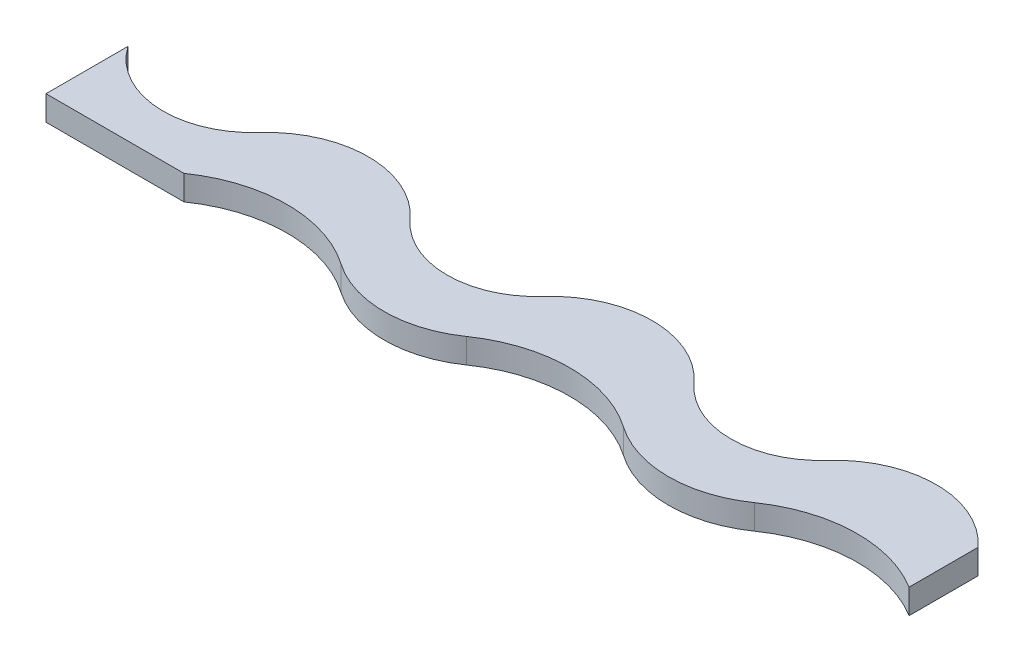
SolidWorks part; units mm, degrees
ref_plane "Front Plane" through (0, 0, 0) normal (0, 0, 1) x (1, 0, 0)
ref_plane "Top Plane" through (0, 0, 0) normal (0, 1, 0) x (1, 0, 0)
ref_plane "Right Plane" through (0, 0, 0) normal (1, 0, 0) x (0, 0, -1)
sketch "Sketch2" plane through (0, 0, 0) normal (0, 1, 0) x (1, 0, 0)
  line L0 (11.15, 0) -> (0, 0) construction
  line L1 (0, 0) -> (0, 6.63)
  line L2 (0, 0) -> (11.15, 0)
  line L3 (69.4199, 0.343) -> (69.4199, 5.91)
  arc A0 (11.3467, 5.91) -> (0, 6.63) centre (5.9583, 10.7605) cw
  arc A1 (11.3467, 5.91) -> (23.5199, 5.91) centre (17.4333, 0.431) cw
  arc A2 (23.5199, 5.91) -> (34.2967, 5.91) centre (28.9083, 10.7605) ccw
  arc A3 (11.15, 0) -> (23.8477, 0) centre (17.4989, -9.1355) cw
  arc A4 (23.8477, 0) -> (33.9831, 0) centre (28.9154, 7.292) ccw
  arc A5 (34.2967, 5.91) -> (46.4699, 5.91) centre (40.3833, 0.431) cw
  arc A6 (33.9831, 0) -> (46.6808, 0) centre (40.3319, -9.1355) cw
  arc A7 (46.6808, 0) -> (57.2467, 0) centre (51.9637, 7.6018) ccw
  arc A8 (57.2467, 0) -> (69.4199, 0.343) centre (63.5956, -9.1355) cw
  arc A9 (46.4699, 5.91) -> (57.2467, 5.91) centre (51.8583, 10.7605) ccw
  arc A10 (57.2467, 5.91) -> (69.4199, 5.91) centre (63.3333, 0.431) cw
  circle A11 centre (5.9583, 10.7605) radius 7
  circle A12 centre (17.4989, -9.1355) radius 10.875
  circle A13 centre (28.9083, 10.7605) radius 7
  circle A14 centre (51.8583, 10.7605) radius 7
  circle A15 centre (40.3319, -9.1355) radius 10.875
  circle A16 centre (63.5956, -9.1355) radius 10.875
  point P25 (0, 0)
  point P26 (0, 0)
  point P31 (0, 0)
  point P34 (0, 0)
  point P40 (0, 0)
  dimension "D1" = 7.25
  dimension "D2" = 11.125
  dimension "D3" = 14
  dimension "D6" = 14
  dimension "D9" = 21.75
  dimension "D11" = 8.88
  dimension "D12" = 14
  dimension "D4" = 6.63
  dimension "D5" = 11.15
  dimension "D7" = 12.3
  dimension "D8" = 0.72
  dimension "D10" = 19.74
  dimension "D13" = 22.95
extrude "Boss-Extrude1" add sketch "Sketch2" along normal blind 2 contours L1 A0 A1 A2 A5 A9 A10 L3 A8 A7 A6 A4 A3 L2
